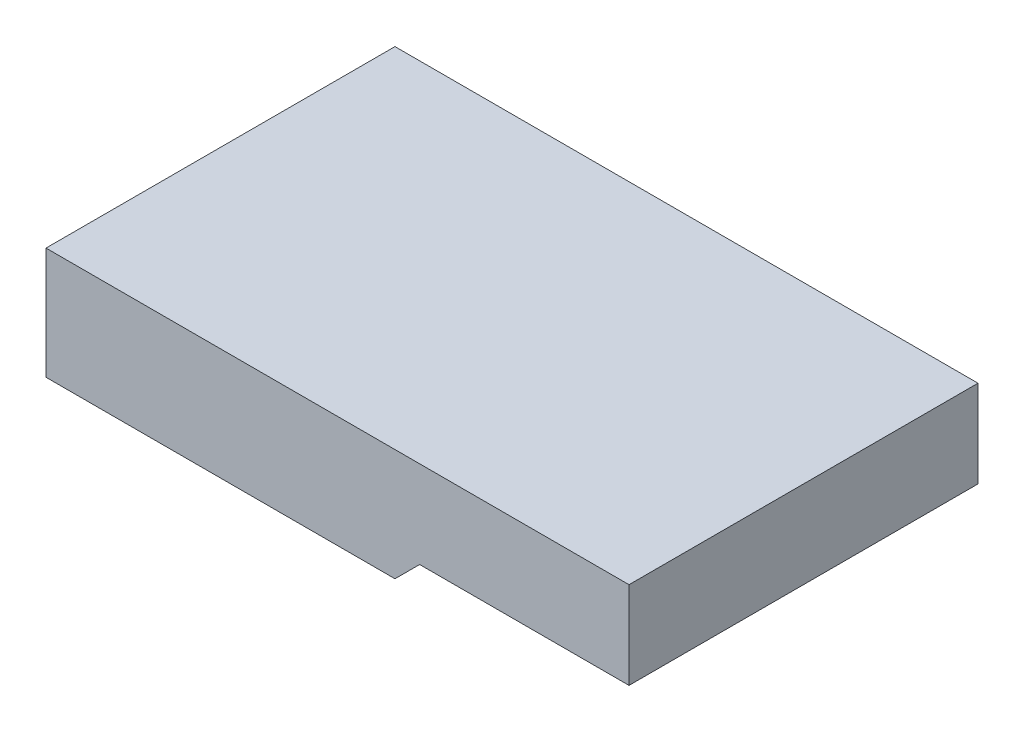
SolidWorks part; units mm, degrees
ref_plane "Plan de face" through (0, 0, 0) normal (0, 0, 1) x (1, 0, 0)
ref_plane "Plan de dessus" through (0, 0, 0) normal (0, 1, 0) x (1, 0, 0)
ref_plane "Plan de droite" through (0, 0, 0) normal (1, 0, 0) x (0, 0, -1)
sketch "Sketch1" plane through (0, 0, 0) normal (0, 0, 1) x (1, 0, 0)
  line L0 (0, 0) -> (10, 0)
  line L1 (10, 0) -> (10.7071, 0.7071)
  line L2 (10.7071, 0.7071) -> (16.7071, 0.7071)
  line L3 (16.7071, 0.7071) -> (16.7071, 3.2071)
  line L4 (16.7071, 3.2071) -> (0, 3.2071)
  line L5 (0, 3.2071) -> (0, 0)
extrude "Boss-Extrude1" add sketch "Sketch1" along normal blind 10
